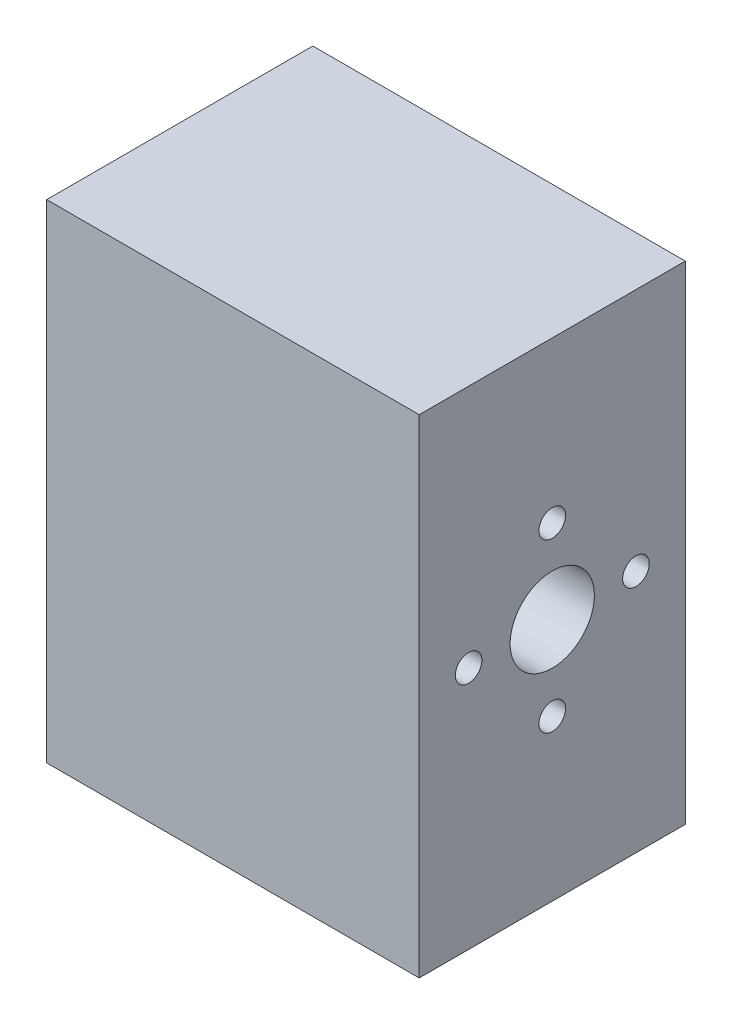
SolidWorks part; units mm, degrees
material "Бальза"
ref_plane "Спереди" through (0, 0, 0) normal (0, 0, 1) x (1, 0, 0)
ref_plane "Сверху" through (0, 0, 0) normal (0, 1, 0) x (1, 0, 0)
ref_plane "Справа" through (0, 0, 0) normal (1, 0, 0) x (0, 0, -1)
sketch "Эскиз1" plane through (0, 0, 0) normal (0, 0, 1) x (1, 0, 0)
  line L1 (0, 0) -> (42, 0)
  line L2 (0, 0) -> (0, 55)
  line L3 (0, 55) -> (42, 55)
  line L4 (42, 0) -> (42, 55)
  dimension "D1" = 42
  dimension "D2" = 55
extrude "Бобышка-Вытянуть1" add sketch "Эскиз1" along normal blind 30
sketch "Эскиз2" plane through (42, 0, 0) normal (1, 0, 0) x (0, 0, -1)
  line L0 (-15, 55) -> (-15, 0) construction
  line L1 (-30, 27.5) -> (0, 27.5) construction
  line L2 (-30, 0) -> (-30, 55) construction
  line L3 (0, 0) -> (0, 55) construction
  line L4 (-30, 0) -> (0, 0) construction
  line L5 (-30, 55) -> (0, 55) construction
  circle A0 centre (-15, 27.5) radius 4.75
  circle A2 centre (-15, 36.9345) radius 1.5
  circle A3 centre (-5.5655, 27.5) radius 1.5
  circle A4 centre (-15, 18.0655) radius 1.5
  circle A5 centre (-24.4345, 27.5) radius 1.5
  dimension "D1" = 9.5
  dimension "D2" = 3
  dimension "D3" = 3
  dimension "D4" = 3
  dimension "D5" = 3
extrude "Вырез-Вытянуть1" cut sketch "Эскиз2" against normal through all
